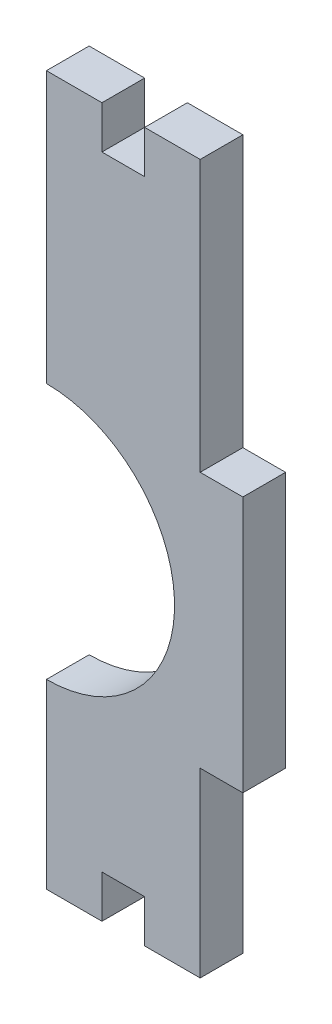
SolidWorks part; units mm, degrees
ref_plane "Plan de face" through (0, 0, 0) normal (0, 0, 1) x (1, 0, 0)
ref_plane "Plan de dessus" through (0, 0, 0) normal (0, 1, 0) x (1, 0, 0)
ref_plane "Plan de droite" through (0, 0, 0) normal (1, 0, 0) x (0, 0, -1)
sketch "Esquisse1" plane through (0, 0, 0) normal (0, 0, 1) x (1, 0, 0)
  line L0 (-18, 35.4361) -> (0, 35.4361)
  line L1 (0, 35.4361) -> (0, -47.5639)
  line L2 (0, -47.5639) -> (-18, -47.5639)
  line L4 (-18, -47.5639) -> (-18, -26.2889)
  line L5 (-18, 35.4361) -> (-18, 3.7111)
  arc A1 (-18, -26.2889) -> (-18, 3.7111) centre (-18, -11.2889) ccw
  dimension "D1" = 15
  dimension "D2" = 36.275
  dimension "D3" = 18
extrude "Boss.-Extru.1" add sketch "Esquisse1" along normal blind 5
sketch "Esquisse2" plane through (0, 0, 5) normal (0, 0, 1) x (1, 0, 0)
  line L0 (0, 35.4361) -> (-18, 35.4361) construction
  line L1 (-11.5, 35.4361) -> (-6.5, 35.4361)
  line L2 (-11.5, 35.4361) -> (-11.5, 30.4361)
  line L3 (-11.5, 30.4361) -> (-6.5, 30.4361)
  line L4 (-6.5, 35.4361) -> (-6.5, 30.4361)
  line L5 (-18, 35.4361) -> (-18, 3.7111) construction
  line L6 (0, -6.0639) -> (41.2224, -6.0639) construction
  line L7 (0, -47.5639) -> (0, 35.4361) construction
  line L8 (-6.5, -47.5639) -> (-6.5, -42.5639)
  line L9 (-11.5, -42.5639) -> (-6.5, -42.5639)
  line L10 (-11.5, -47.5639) -> (-11.5, -42.5639)
  line L11 (-11.5, -47.5639) -> (-6.5, -47.5639)
  dimension "D1" = 5
  dimension "D2" = 5
  dimension "D3" = 6.5
extrude "Enlèv. mat.-Extru.1" cut sketch "Esquisse2" against normal blind 5
sketch "Esquisse3" plane through (0, 0, 5) normal (0, 0, 1) x (1, 0, 0)
  line L0 (0, -47.5639) -> (0, 35.4361) construction
  line L1 (0, 3.7111) -> (5, 3.7111)
  line L2 (0, 3.7111) -> (0, -26.2889)
  line L3 (0, -26.2889) -> (5, -26.2889)
  line L4 (5, 3.7111) -> (5, -26.2889)
  line L5 (5, 35.4361) -> (5, -47.5639) construction
  line L6 (-18, -11.2889) -> (5, -11.2889) construction
  dimension "D1" = 30
extrude "Boss.-Extru.2" add sketch "Esquisse3" against normal blind 5
